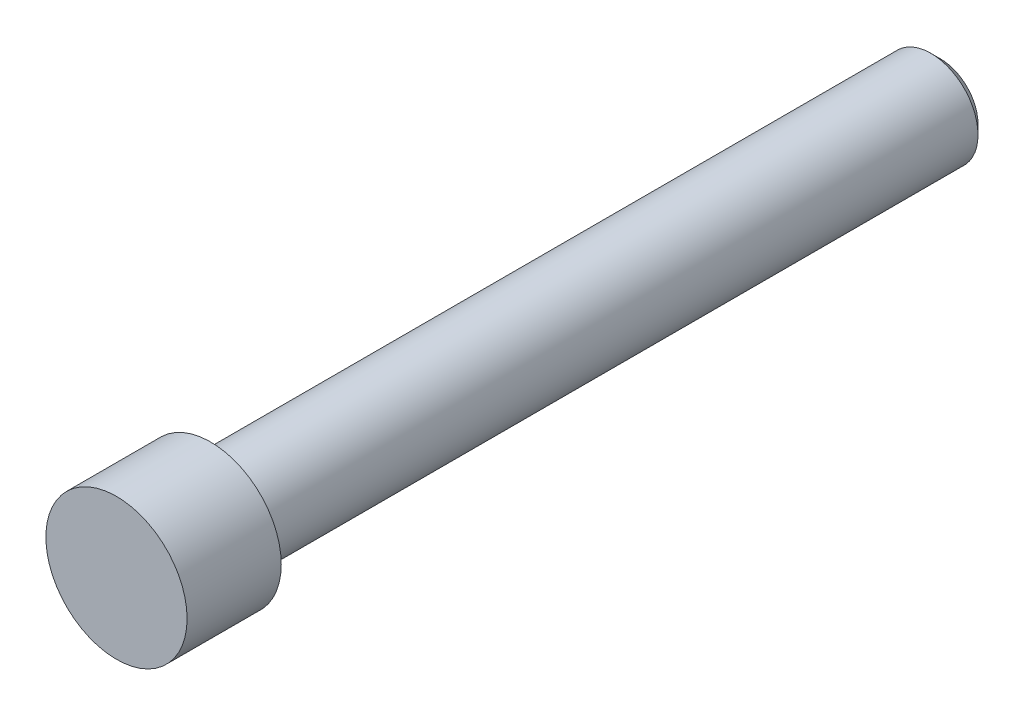
SolidWorks part; units mm, degrees
ref_plane "Alzado" through (0, 0, 0) normal (0, 0, 1) x (1, 0, 0)
ref_plane "Planta" through (0, 0, 0) normal (0, 1, 0) x (1, 0, 0)
ref_plane "Vista lateral" through (0, 0, 0) normal (1, 0, 0) x (0, 0, -1)
sketch "Croquis1" plane through (0, 0, 0) normal (0, 0, 1) x (1, 0, 0)
  circle A0 centre (0, 0) radius 1
  dimension "D1" = 2
extrude "Saliente-Extruir1" add sketch "Croquis1" along normal blind 15.5
sketch "Croquis2" plane through (0, 0, 15.5) normal (0, 0, 1) x (1, 0, 0)
  circle A0 centre (0, 0) radius 1.5
  dimension "D1" = 3
extrude "Saliente-Extruir2" add sketch "Croquis2" along normal blind 2
chamfer "Chaflán1" distance 0.2 angle 45 1 edges at (1, 0, 0)
